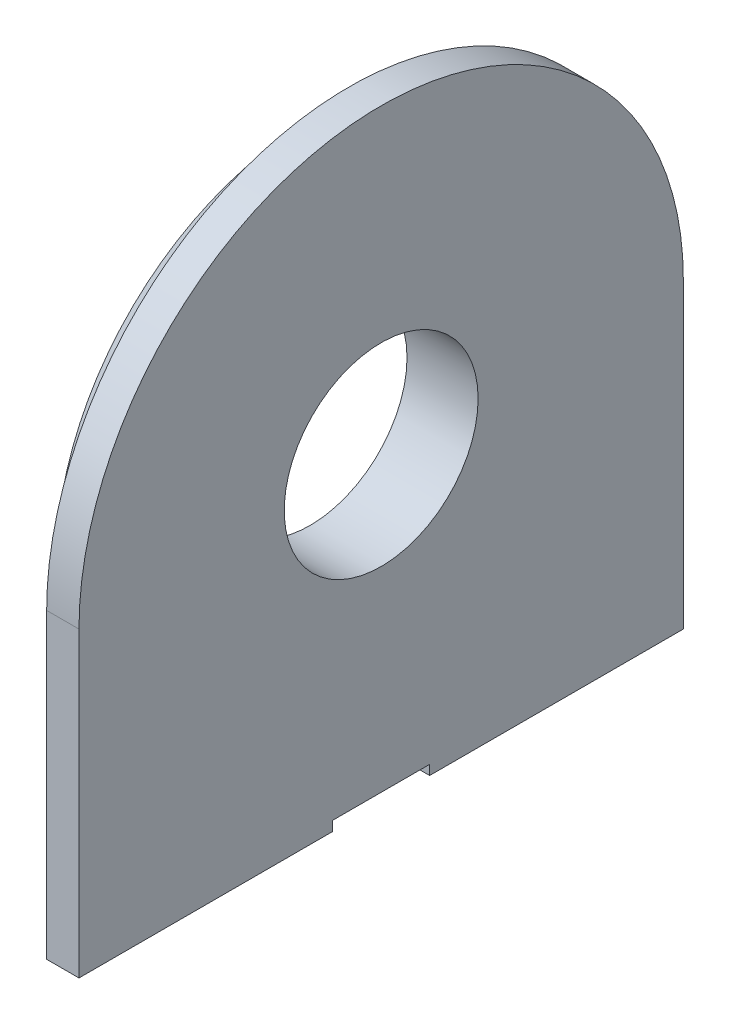
SolidWorks part; units mm, degrees
ref_plane "Спереди" through (0, 0, 0) normal (0, 0, 1) x (1, 0, 0)
ref_plane "Сверху" through (0, 0, 0) normal (0, 1, 0) x (1, 0, 0)
ref_plane "Справа" through (0, 0, 0) normal (1, 0, 0) x (0, 0, -1)
sketch "Эскиз1" plane through (18.5, 0, 0) normal (1, 0, 0) x (0, 0, -1)
  line L0 (1.5, -9.05) -> (-1.5, -9.05) construction
  line L1 (1.3, -9.05) -> (-1.3, -9.05)
  line L2 (1.5, -9.35) -> (1.5, -8.4174) construction
  line L3 (-1.5, -8.4174) -> (-1.5, -9.35) construction
  line L4 (1.5, -9.05) -> (1.5, -8.4174) construction
  line L5 (-1.5, -8.4174) -> (-1.5, -9.05) construction
  line L6 (-1.3, -8.4174) -> (-1.3, -9.05)
  line L7 (1.3, -9.05) -> (1.3, -8.4174)
  line L8 (-1.3, -8.4174) -> (-1.3, -8.2482)
  line L9 (1.3, -8.4174) -> (1.3, -8.2482)
  line L10 (-1.3, -9.05) -> (-1.5, -9.05) construction
  line L11 (1.5, -9.05) -> (1.3, -9.05) construction
  arc A0 (-1.3, -8.2482) -> (1.3, -8.2482) centre (0, 0) ccw construction
  circle A1 centre (0, 0) radius 3 construction
  arc A2 (1.4649, -8.2205) -> (-1.4649, -8.2205) centre (0, 0) ccw
  arc A3 (1.3, -8.2482) -> (-1.3, -8.2482) centre (0, 0) ccw
  circle A4 centre (0, 0) radius 3
  point P14 (0, 0)
  dimension "D1" = 0.2
  dimension "D2" = 0.2
extrude "Бобышка-Вытянуть1" add sketch "Эскиз1" against normal blind 1.2
chamfer "Фаска1" distance 0.5 angle 45 1 edges at (17.3, 8.35, 0)
sketch "Эскиз2" plane through (18.5, 0, 0) normal (1, 0, 0) x (0, 0, -1)
  line L2 (1.5, -9.05) -> (-1.5, -9.05) construction
  line L4 (1.5, -9.05) -> (-1.5, -9.05)
  line L5 (-1.5, -9.05) -> (-1.5, -8.4174) construction
  line L6 (1.5, -8.4174) -> (1.5, -9.05) construction
  line L7 (-1.5, -9.35) -> (-1.5, -8.4174)
  line L8 (1.5, -8.4174) -> (1.5, -9.35)
  line L9 (1.5, -9.35) -> (9.35, -9.35)
  line L10 (9.35, -9.35) -> (9.35, 0)
  line L11 (-9.35, 0) -> (-9.35, -9.35)
  line L12 (-9.35, -9.35) -> (-1.5, -9.35)
  line L13 (-1.5, -9.35) -> (-1.5, -9.05)
  line L14 (1.5, -9.05) -> (1.5, -9.35)
  line L15 (1.5, -9.35) -> (9.35, -9.35)
  line L16 (9.35, -9.35) -> (9.35, 0)
  line L17 (-9.35, 0) -> (-9.35, -9.35)
  line L18 (-9.35, -9.35) -> (-1.5, -9.35)
  circle A0 centre (0, 0) radius 3 construction
  circle A1 centre (0, 0) radius 3
  arc A2 (1.5, -8.4174) -> (-1.5, -8.4174) centre (0, 0) ccw
  arc A3 (9.35, 0) -> (-9.35, 0) centre (0, 0) ccw
  arc A5 (9.35, 0) -> (-9.35, 0) centre (0, 0) ccw
  dimension "D1" = 0
extrude "Бобышка-Вытянуть2" add sketch "Эскиз2" along normal blind 1
